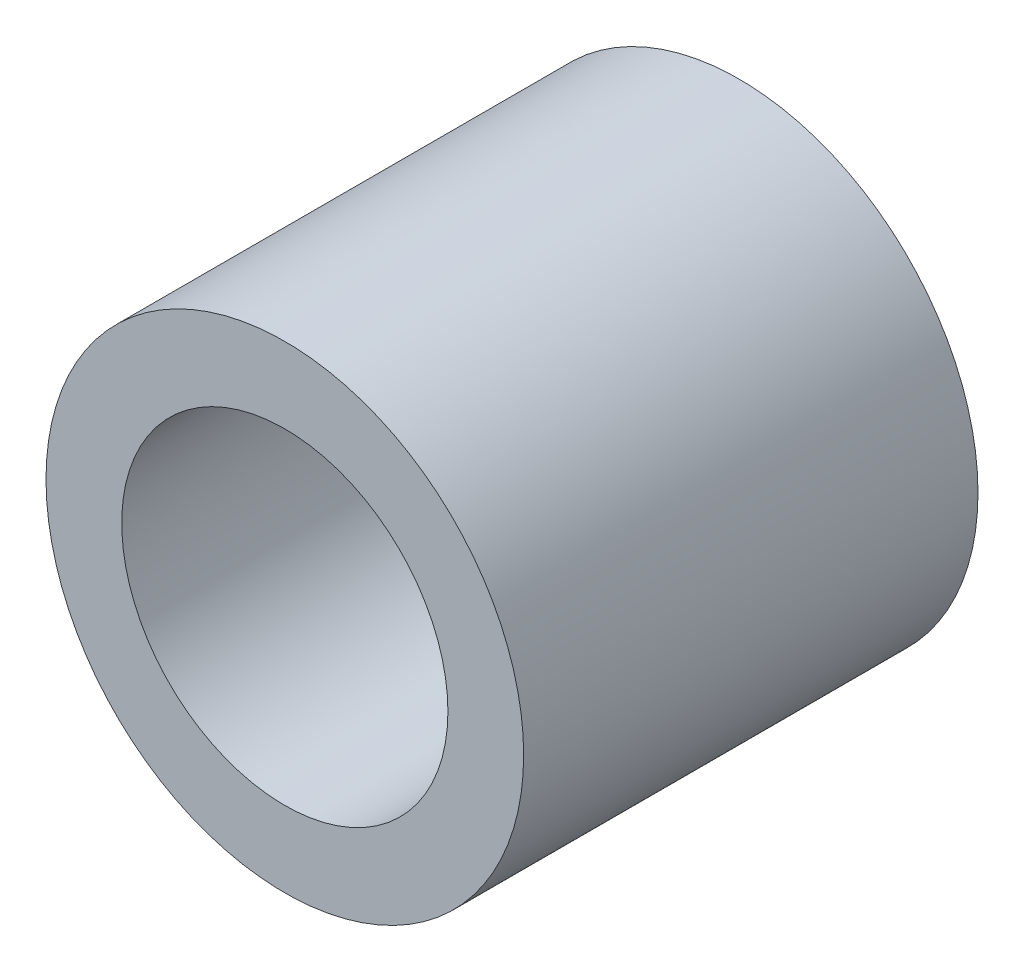
SolidWorks part; units mm, degrees
material "Nylon 6/10"
ref_plane "Front Plane" through (0, 0, 0) normal (0, 0, 1) x (1, 0, 0)
ref_plane "Top Plane" through (0, 0, 0) normal (0, 1, 0) x (1, 0, 0)
ref_plane "Right Plane" through (0, 0, 0) normal (1, 0, 0) x (0, 0, -1)
sketch "Sketch1" plane through (0, 0, 0) normal (0, 0, 1) x (1, 0, 0)
  circle A0 centre (0, 0) radius 1.4
  circle A1 centre (0, 0) radius 2.05
  dimension "D1" = 2.8
  dimension "D2" = 4.1
extrude "Boss-Extrude1" add sketch "Sketch1" along normal blind 3.9
